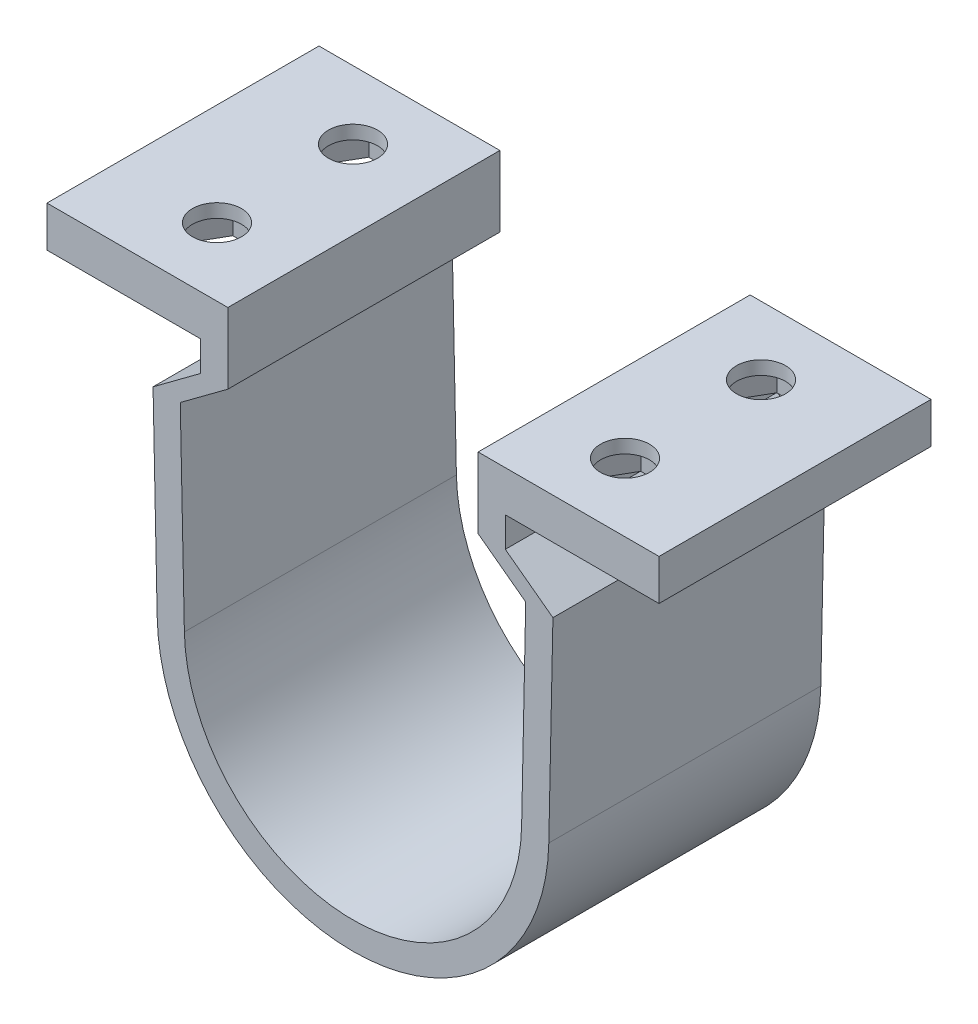
SolidWorks part; units mm, degrees
ref_plane "Front Plane" through (0, 0, 0) normal (0, 0, 1) x (1, 0, 0)
ref_plane "Top Plane" through (0, 0, 0) normal (0, 1, 0) x (1, 0, 0)
ref_plane "Right Plane" through (0, 0, 0) normal (1, 0, 0) x (0, 0, -1)
sketch "Sketch1" plane through (0, 0, 0) normal (0, 0, 1) x (1, 0, 0)
  line L0 (-22.5, 19) -> (-11.2, 19)
  line L1 (-14.7004, 14.2) -> (-14.3968, -0.3014)
  line L6 (-22.5, 19) -> (-22.5, 22)
  line L7 (-22.5, 22) -> (-9.2, 22)
  line L8 (-12.7, 14.2) -> (-12.3973, -0.2595)
  line L10 (-13.0466, 30.7547) -> (-12.3973, -0.2595) construction
  line L11 (12.4, 0) -> (12.4, 19) construction
  line L12 (0, 0) -> (0, 53.7575) construction
  line L13 (12.5, 14.2) -> (-12.5, 14.2) construction
  line L14 (-9, 14.2) -> (-9, 22.2) construction
  line L15 (-9, 22.2) -> (-22.5, 22.2) construction
  line L16 (-15, 27.2) -> (-15, 17.2) construction
  line L18 (-9.2, 16.7997) -> (-12.7, 14.2)
  line L21 (-15.0461, 30.7128) -> (-14.3968, -0.3014) construction
  line L23 (-12.25, 21) -> (-17.75, 21) construction
  line L25 (-9.2, 22) -> (-9.2, 16.7997)
  line L26 (-14.7004, 14.2) -> (-11.2, 16.8)
  line L27 (-11.2, 16.8) -> (-11.2, 19)
  line L29 (14.4, 0) -> (14.4, 19) construction
  line L30 (12.7, 14.2) -> (12.3973, -0.2595)
  line L31 (9.2, 16.7997) -> (12.7, 14.2)
  line L32 (9.2, 22) -> (9.2, 16.7997)
  line L33 (22.5, 22) -> (9.2, 22)
  line L34 (22.5, 19) -> (22.5, 22)
  line L35 (22.5, 19) -> (11.2, 19)
  line L36 (11.2, 16.8) -> (11.2, 19)
  line L37 (14.7004, 14.2) -> (11.2, 16.8)
  line L38 (14.7004, 14.2) -> (14.3968, -0.3014)
  arc A0 (-14.3968, -0.3014) -> (14.3968, -0.3014) centre (0, 0) ccw
  arc A1 (-12.3973, -0.2595) -> (12.3973, -0.2595) centre (0, 0) ccw
  circle A2 centre (0, 0) radius 12.2 construction
  arc A4 (-14.3968, -0.3014) -> (14.4, 0) centre (0, 0) ccw construction
  arc A5 (-12.3973, -0.2595) -> (12.4, 0) centre (0, 0) ccw construction
  point P7 (-15, 14.2)
  point P17 (0, 12.2)
  point P22 (0, 14.2)
  point P25 (0, 0)
  point P29 (-15, 22.2)
  point P30 (-12.7, 14.2)
  point P34 (0, 0)
  point P38 (0, 0)
  point P41 (-15, 21)
  dimension "D3" = 24.4
  dimension "D4" = 0.2
  dimension "D2" = 3
  dimension "D5" = 25
  dimension "D6" = 2
  dimension "D7" = 3.5
  dimension "D8" = 8
  dimension "D9" = 13.5
  dimension "D10" = 7.5
  dimension "D11" = 0.2
  dimension "D12" = 0.2
  dimension "D13" = 0.2
  dimension "D14" = 10
  dimension "D15" = 5.5
  dimension "D16" = 2
  dimension "D17" = 1
  dimension "D18" = 2.2
  dimension "D1" = 2
extrude "Boss-Extrude1" add sketch "Sketch1" along normal blind 20
sketch "Sketch4" plane through (0, 19, 0) normal (0, -1, 0) x (1, 0, 0)
  line L0 (0, 0) -> (0, 20) construction
  line L1 (-13.4123, 2.25) -> (-11.8246, 5)
  line L2 (-11.8246, 5) -> (-13.4123, 7.75)
  line L3 (-13.4123, 7.75) -> (-16.5877, 7.75)
  line L4 (-16.5877, 7.75) -> (-18.1754, 5)
  line L5 (-18.1754, 5) -> (-16.5877, 2.25)
  line L6 (-16.5877, 2.25) -> (-13.4123, 2.25)
  line L7 (-11.8246, 15) -> (-13.4123, 17.75)
  line L8 (-13.4123, 17.75) -> (-16.5877, 17.75)
  line L9 (-16.5877, 17.75) -> (-18.1754, 15)
  line L10 (-18.1754, 15) -> (-16.5877, 12.25)
  line L11 (-16.5877, 12.25) -> (-13.4123, 12.25)
  line L12 (-13.4123, 12.25) -> (-11.8246, 15)
  line L13 (-14.3968, 0) -> (14.3968, 0) construction
  line L14 (14.3968, 20) -> (-14.3968, 20) construction
  line L15 (-22.5, 0) -> (-11.2, 0) construction
  line L16 (-22.5, 20) -> (-22.5, 0) construction
  line L17 (13.4123, 12.25) -> (11.8246, 15)
  line L18 (16.5877, 12.25) -> (13.4123, 12.25)
  line L19 (18.1754, 15) -> (16.5877, 12.25)
  line L20 (16.5877, 17.75) -> (18.1754, 15)
  line L21 (13.4123, 17.75) -> (16.5877, 17.75)
  line L22 (11.8246, 15) -> (13.4123, 17.75)
  line L23 (16.5877, 2.25) -> (13.4123, 2.25)
  line L24 (18.1754, 5) -> (16.5877, 2.25)
  line L25 (16.5877, 7.75) -> (18.1754, 5)
  line L26 (13.4123, 7.75) -> (16.5877, 7.75)
  line L27 (11.8246, 5) -> (13.4123, 7.75)
  line L28 (13.4123, 2.25) -> (11.8246, 5)
  circle A0 centre (-15, 5) radius 2.75 construction
  circle A1 centre (-15, 15) radius 2.75 construction
  point P22 (-18.624, 4.5565)
  point P23 (0, 0)
  point P26 (-18.3144, 4.0333)
  point P31 (-14.147, -0.3456)
  dimension "D1" = 5.5
  dimension "D2" = 10
  dimension "D3" = 7.5
  dimension "D4" = 5
extrude "Cut-Extrude1" cut sketch "Sketch4" against normal blind 2
sketch "Sketch5" plane through (0, 19, 0) normal (0, -1, 0) x (-1, 0, 0)
  line L0 (0, -20) -> (0, 0) construction
  line L1 (-14.3968, -20) -> (14.3968, -20) construction
  line L3 (-22.5, -10) -> (22.5, -10) construction
  line L4 (-22.5, -20) -> (-22.5, 0) construction
  line L5 (22.5, -20) -> (22.5, 0) construction
  line L7 (-15, -15) -> (-17.3816, -13.625) construction
  line L8 (-16.5877, -12.25) -> (-18.1754, -15) construction
  line L10 (-15, -15) -> (-15, -12.25) construction
  line L11 (-13.4123, -12.25) -> (-16.5877, -12.25) construction
  point P0 (-15, -15)
  point P39 (-15, -14.9096)
  point P40 (0, 0)
  point P41 (15, -15)
  point P42 (0, 0)
  point P43 (-15, -5)
  point P44 (15, -5)
hole_wizard "M3 Clearance Hole1" positions "Sketch5" profile "Sketch6" hole size "M3" standard "ANSI Metric"
sketch "Sketch6" plane through (15, 19, 15) normal (1, 0, 0) x (0, 0, -1)
  line L0 (0, 0) -> (0, 3)
  line L1 (0, 3) -> (1.8, 3)
  line L2 (1.8, 3) -> (1.8, 0)
  line L5 (1.8, 0) -> (0, 0)
  line L11 (0, -6.35) -> (0, 107.95) construction
  dimension "Thru Hole Dia." = 3.6
  dimension "Thru Hole Depth" = 3
